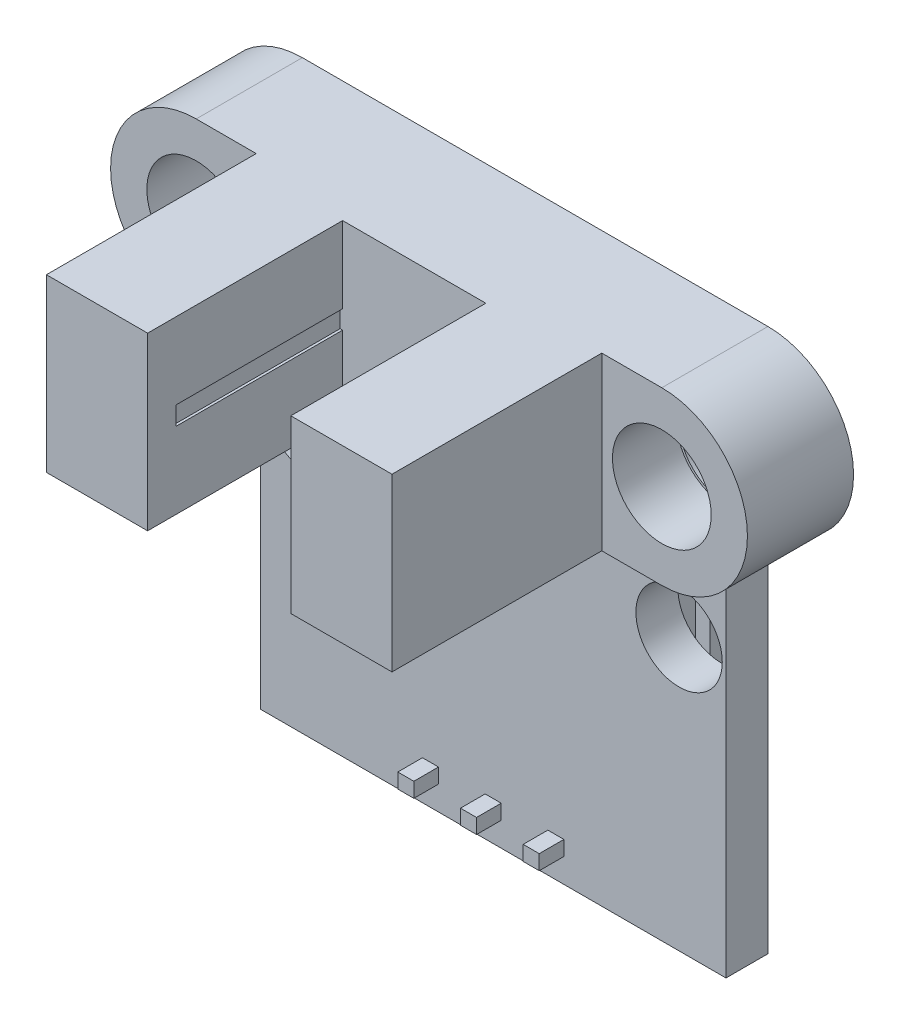
SolidWorks part; units mm, degrees
ref_plane "Ön Düzlem" through (0, 0, 0) normal (0, 0, 1) x (1, 0, 0)
ref_plane "Üst Düzlem" through (0, 0, 0) normal (0, 1, 0) x (1, 0, 0)
ref_plane "Sağ Düzlem" through (0, 0, 0) normal (1, 0, 0) x (0, 0, -1)
sketch "Çizim1" plane through (0, 0, 0) normal (0, 0, 1) x (1, 0, 0)
  line L0 (9.432, -11) -> (7.5313, -11) construction
  line L1 (-9.432, -11) -> (9.432, -11)
  line L2 (-9.432, -11) -> (-9.432, 4.0626)
  line L3 (-9.432, 11) -> (9.432, 11)
  line L4 (9.432, -11) -> (9.432, 4.0626)
  line L5 (7.5313, -11) -> (7.5313, 0) construction
  line L9 (0, 11) -> (0, -11) construction
  arc A0 (9.432, 4.0626) -> (9.432, 11) centre (9.432, 7.5313) ccw
  circle A1 centre (9.432, 7.5313) radius 1.9006
  circle A2 centre (-9.432, 7.5313) radius 1.9006
  arc A3 (-9.432, 4.0626) -> (-9.432, 11) centre (-9.432, 7.5313) cw
  circle A4 centre (7.5313, 0) radius 1.75
  circle A5 centre (-7.5313, 0) radius 1.75
  point P0 (0, 0)
  dimension "D1" = 22
  dimension "D3" = 3.5
  dimension "D2" = 11
extrude "Yükseklik-Ekstrüzyon1" add sketch "Çizim1" along normal blind 1.7
sketch "Çizim2" plane through (0, 0, 1.7) normal (0, 0, 1) x (1, 0, 0)
  line L0 (-9.432, 11) -> (9.432, 11)
  line L1 (9.432, 4.0626) -> (-9.432, 4.0626)
  line L2 (9.432, 11) -> (-9.432, 11) construction
  arc A0 (9.432, 4.0626) -> (9.432, 11) centre (9.432, 7.5313) ccw
  arc A1 (-9.432, 11) -> (-9.432, 4.0626) centre (-9.432, 7.5313) ccw
  circle A2 centre (-9.432, 7.5313) radius 2
  circle A3 centre (9.432, 7.5313) radius 2
extrude "Yükseklik-Ekstrüzyon2" add sketch "Çizim2" along normal blind 2.6
sketch "Çizim3" plane through (0, 0, 4.3) normal (0, 0, 1) x (1, 0, 0)
  line L0 (9.432, 11) -> (-9.432, 11) construction
  line L2 (-9.432, 4.0626) -> (9.432, 4.0626) construction
  line L3 (2.9, 4.0626) -> (7.0001, 4.0626)
  line L4 (-7.0001, 11) -> (-2.9, 11)
  line L5 (-7.0001, 11) -> (-7.0001, 4.0626)
  line L6 (-7.0001, 4.0626) -> (-2.9, 4.0626)
  line L7 (7.0001, 11) -> (7.0001, 4.0626)
  line L11 (-2.9, 11) -> (-2.9, 4.0626)
  line L13 (2.9, 11) -> (2.9, 4.0626)
  line L18 (2.9, 11) -> (7.0001, 11)
  point P6 (0, 7.925)
  point P11 (0, 7.925)
  dimension "D1" = 5.8
extrude "Yükseklik-Ekstrüzyon3" add sketch "Çizim3" along normal blind 8.5
sketch "Çizim4" plane through (0, 0, 4.3) normal (0, 0, 1) x (1, 0, 0)
  line L4 (2.9, 11) -> (-2.9, 11)
  line L5 (-2.9, 11) -> (-2.9, 4.0626)
  line L6 (-2.9, 4.0626) -> (2.9, 4.0626)
  line L7 (2.9, 4.0626) -> (2.9, 11)
  line L8 (2.9, 11) -> (-2.9, 11)
  line L9 (-2.9, 11) -> (-2.9, 4.0626)
  line L10 (-2.9, 4.0626) -> (2.9, 4.0626)
  line L11 (2.9, 4.0626) -> (2.9, 11)
  dimension "D1" = 0
extrude "Yükseklik-Ekstrüzyon4" add sketch "Çizim4" along normal blind 0.6
sketch "Çizim5" plane through (0, 0, 0) normal (0, 0, -1) x (-1, 0, 0)
  line L0 (9.432, -11) -> (-9.432, -11) construction
  line L5 (0, -11) -> (0, -8.46) construction
  line L6 (1.02, -8.46) -> (1.27, -8.71)
  line L8 (-1.02, -8.46) -> (1.02, -8.46)
  line L9 (-1.27, -8.71) -> (-1.27, -10.75)
  line L10 (-1.02, -11) -> (1.02, -11)
  line L11 (1.27, -8.71) -> (1.27, -10.75)
  line L12 (-1.27, -8.46) -> (1.27, -11) construction
  line L13 (-1.27, -11) -> (1.27, -8.46) construction
  line L14 (1.02, -11) -> (1.27, -10.75)
  line L15 (-1.27, -10.75) -> (-1.02, -11)
  line L16 (-1.27, -8.71) -> (-1.02, -8.46)
  line L17 (-1.52, -11) -> (-3.56, -11)
  line L18 (-3.56, -11) -> (-3.81, -10.75)
  line L19 (-3.81, -8.71) -> (-3.81, -10.75)
  line L20 (-3.56, -8.46) -> (-3.81, -8.71)
  line L21 (-1.52, -8.46) -> (-3.56, -8.46)
  line L22 (-1.27, -10.75) -> (-1.52, -11)
  line L23 (-1.27, -8.71) -> (-1.52, -8.46)
  line L24 (3.56, -11) -> (1.52, -11)
  line L25 (1.52, -11) -> (1.27, -10.75)
  line L26 (1.52, -8.46) -> (1.27, -8.71)
  line L27 (3.56, -8.46) -> (1.52, -8.46)
  line L28 (3.81, -10.75) -> (3.56, -11)
  line L29 (3.81, -8.71) -> (3.56, -8.46)
  line L30 (3.81, -8.71) -> (3.81, -10.75)
  point P0 (0, -11)
  point P3 (0, -9.73)
  line M15 (-9.432, -11) -> (9.432, -11)
extrude "Yükseklik-Ekstrüzyon6" add sketch "Çizim5" along normal blind 2.54 contours L9 L23 L21 L20 L19 L18 L22 M15 | L16 L9 L15 L14 L11 L6 L8 M15 | L30 L29 L27 L26 L11 L25 L28 M15
sketch "Çizim6" plane through (0, -11, 0) normal (0, -1, 0) x (1, 0, 0)
  line L1 (-9.432, 1.7) -> (9.432, 1.7)
  line L2 (-9.432, 1.7) -> (-9.432, 0)
  line L3 (-9.432, 0) -> (9.432, 0)
  line L4 (9.432, 1.7) -> (9.432, 0)
extrude "Yükseklik-Ekstrüzyon7" add sketch "Çizim6" along normal blind 0.01
sketch "Çizim7" plane through (2.9, 0, 0) normal (-1, 0, 0) x (0, 0, 1)
  line L0 (4.9, 7.5313) -> (11.65, 7.5313) construction
  line L1 (4.9, 4.0626) -> (4.9, 11) construction
  line L3 (4.9, 7.9063) -> (11.65, 7.9063)
  line L4 (4.9, 7.9063) -> (4.9, 7.1563)
  line L5 (4.9, 7.1563) -> (11.65, 7.1563)
  line L6 (11.65, 7.9063) -> (11.65, 7.1563)
  line L7 (4.9, 7.9063) -> (11.65, 7.1563) construction
  line L8 (4.9, 7.1563) -> (11.65, 7.9063) construction
  point P4 (8.275, 7.5313)
extrude "Kes-Ekstrüzyon1" cut sketch "Çizim7" against normal blind 0.1 and the other way blind 5.9
sketch "Çizim8" plane through (0, 0, -2.54) normal (0, 0, -1) x (-1, 0, 0)
  line L0 (-1.27, -8.71) -> (-1.27, -10.75) construction
  line L3 (1.27, -8.71) -> (1.27, -10.75) construction
  line L4 (1.145, -10.875) -> (-1.145, -8.585) construction
  line L5 (1.02, -11) -> (1.27, -10.75) construction
  line L6 (-1.27, -8.71) -> (-1.02, -8.46) construction
  line L7 (2.8725, -9.3975) -> (2.2075, -9.3975)
  line L8 (-0.3325, -10.0625) -> (0.3325, -10.0625)
  line L9 (-0.3325, -10.0625) -> (-0.3325, -9.3975)
  line L10 (-0.3325, -9.3975) -> (0.3325, -9.3975)
  line L11 (0.3325, -10.0625) -> (0.3325, -9.3975)
  line L12 (-0.3325, -10.0625) -> (0.3325, -9.3975) construction
  line L13 (-0.3325, -9.3975) -> (0.3325, -10.0625) construction
  line L14 (2.2075, -10.0625) -> (2.2075, -9.3975)
  line L15 (2.8725, -10.0625) -> (2.2075, -10.0625)
  line L16 (2.8725, -10.0625) -> (2.8725, -9.3975)
  line L17 (-2.2075, -9.3975) -> (-2.8725, -9.3975)
  line L18 (-2.8725, -10.0625) -> (-2.8725, -9.3975)
  line L19 (-2.2075, -10.0625) -> (-2.8725, -10.0625)
  line L20 (-2.2075, -10.0625) -> (-2.2075, -9.3975)
  point P14 (0, -9.73)
ref_plane "Düzlem1" through (0, 0, 0) normal (1, 0, 0) x (0, 0, -1)
sketch "Çizim9" plane through (0, 0, 0) normal (1, 0, 0) x (0, 0, -1)
  line L0 (2.54, -9.73) -> (4.04, -9.73)
  line L1 (4.54, -9.23) -> (4.54, -3.305)
  arc A0 (4.04, -9.73) -> (4.54, -9.23) centre (4.04, -9.23) ccw
  dimension "D1" = 0.5
sweep "Süpür1" add profiles "Çizim8" path "Çizim9"
sketch "Çizim10" plane through (0, 0, -2.54) normal (0, 0, -1) x (-1, 0, 0)
  line L20 (-1.52, -11) -> (-1.27, -10.75)
  line L21 (-1.27, -10.75) -> (-1.02, -11)
  line L22 (-1.02, -11) -> (1.02, -11)
  line L23 (1.02, -11) -> (1.27, -10.75)
  line L24 (1.27, -10.75) -> (1.52, -11)
  line L25 (1.52, -11) -> (3.56, -11)
  line L26 (3.56, -11) -> (3.81, -10.75)
  line L27 (3.81, -10.75) -> (3.81, -8.71)
  line L28 (3.81, -8.71) -> (3.56, -8.46)
  line L29 (3.56, -8.46) -> (1.52, -8.46)
  line L30 (1.52, -8.46) -> (1.27, -8.71)
  line L31 (1.27, -8.71) -> (1.02, -8.46)
  line L32 (1.02, -8.46) -> (-1.02, -8.46)
  line L33 (-1.02, -8.46) -> (-1.27, -8.71)
  line L34 (-1.27, -8.71) -> (-1.52, -8.46)
  line L35 (-1.52, -8.46) -> (-3.56, -8.46)
  line L36 (-3.56, -8.46) -> (-3.81, -8.71)
  line L37 (-3.81, -8.71) -> (-3.81, -10.75)
  line L38 (-3.81, -10.75) -> (-3.56, -11)
  line L39 (-3.56, -11) -> (-1.52, -11)
  line L40 (-1.52, -11) -> (-1.27, -10.75)
  line L41 (-1.27, -10.75) -> (-1.02, -11)
  line L42 (-1.02, -11) -> (1.02, -11)
  line L43 (1.02, -11) -> (1.27, -10.75)
  line L44 (1.27, -10.75) -> (1.52, -11)
  line L45 (1.52, -11) -> (3.56, -11)
  line L46 (3.56, -11) -> (3.81, -10.75)
  line L47 (3.81, -10.75) -> (3.81, -8.71)
  line L48 (3.81, -8.71) -> (3.56, -8.46)
  line L49 (3.56, -8.46) -> (1.52, -8.46)
  line L50 (1.52, -8.46) -> (1.27, -8.71)
  line L51 (1.27, -8.71) -> (1.02, -8.46)
  line L52 (1.02, -8.46) -> (-1.02, -8.46)
  line L53 (-1.02, -8.46) -> (-1.27, -8.71)
  line L54 (-1.27, -8.71) -> (-1.52, -8.46)
  line L55 (-1.52, -8.46) -> (-3.56, -8.46)
  line L56 (-3.56, -8.46) -> (-3.81, -8.71)
  line L57 (-3.81, -8.71) -> (-3.81, -10.75)
  line L58 (-3.81, -10.75) -> (-3.56, -11)
  line L59 (-3.56, -11) -> (-1.52, -11)
  dimension "D1" = 0
sketch "Çizim11" plane through (0, 0, 1.7) normal (0, 0, 1) x (1, 0, 0)
  line L0 (-1.27, -8.71) -> (-1.27, -10.75) construction
  line L1 (0, -8.46) -> (0, -11) construction
  line L2 (-1.02, -8.46) -> (1.02, -8.46) construction
  line L3 (1.02, -11) -> (-1.02, -11) construction
  line L4 (1.27, -8.71) -> (1.27, -10.75) construction
  line L5 (-2.215, -10.03) -> (-2.865, -10.03)
  line L6 (-0.325, -9.43) -> (0.325, -9.43)
  line L7 (-0.325, -9.43) -> (-0.325, -10.03)
  line L8 (-0.325, -10.03) -> (0.325, -10.03)
  line L9 (0.325, -9.43) -> (0.325, -10.03)
  line L10 (-0.325, -9.43) -> (0.325, -10.03) construction
  line L11 (-0.325, -10.03) -> (0.325, -9.43) construction
  line L12 (-2.865, -9.43) -> (-2.865, -10.03)
  line L13 (-2.215, -9.43) -> (-2.865, -9.43)
  line L14 (-2.215, -9.43) -> (-2.215, -10.03)
  line L15 (2.865, -10.03) -> (2.215, -10.03)
  line L16 (2.215, -9.43) -> (2.215, -10.03)
  line L17 (2.865, -9.43) -> (2.215, -9.43)
  line L18 (2.865, -9.43) -> (2.865, -10.03)
  point P14 (0, -9.73)
extrude "Yükseklik-Ekstrüzyon8" add sketch "Çizim11" along normal blind 1
sketch "Çizim12" plane through (0, 0, 0) normal (0, 0, -1) x (-1, 0, 0)
  line L0 (-9.432, 0) -> (-4.9982, 0) construction
  line L1 (-9.432, -11.01) -> (-9.432, 4.0626) construction
  line L2 (-4.9982, 0) -> (-4.9982, 2.3312)
  line L3 (-4.9982, 2.3312) -> (-1.2034, 2.3312)
  line L4 (-1.2034, 2.3312) -> (-1.2034, -3.046)
  line L5 (-1.2034, -3.046) -> (-4.9982, -3.046)
  line L6 (-4.9982, -3.046) -> (-4.9982, 0)
  point P8 (-3.936, 0)
  point P10 (-7.5555, 0.8288)
extrude "Yükseklik-Ekstrüzyon9" add sketch "Çizim12" along normal blind 1.5
